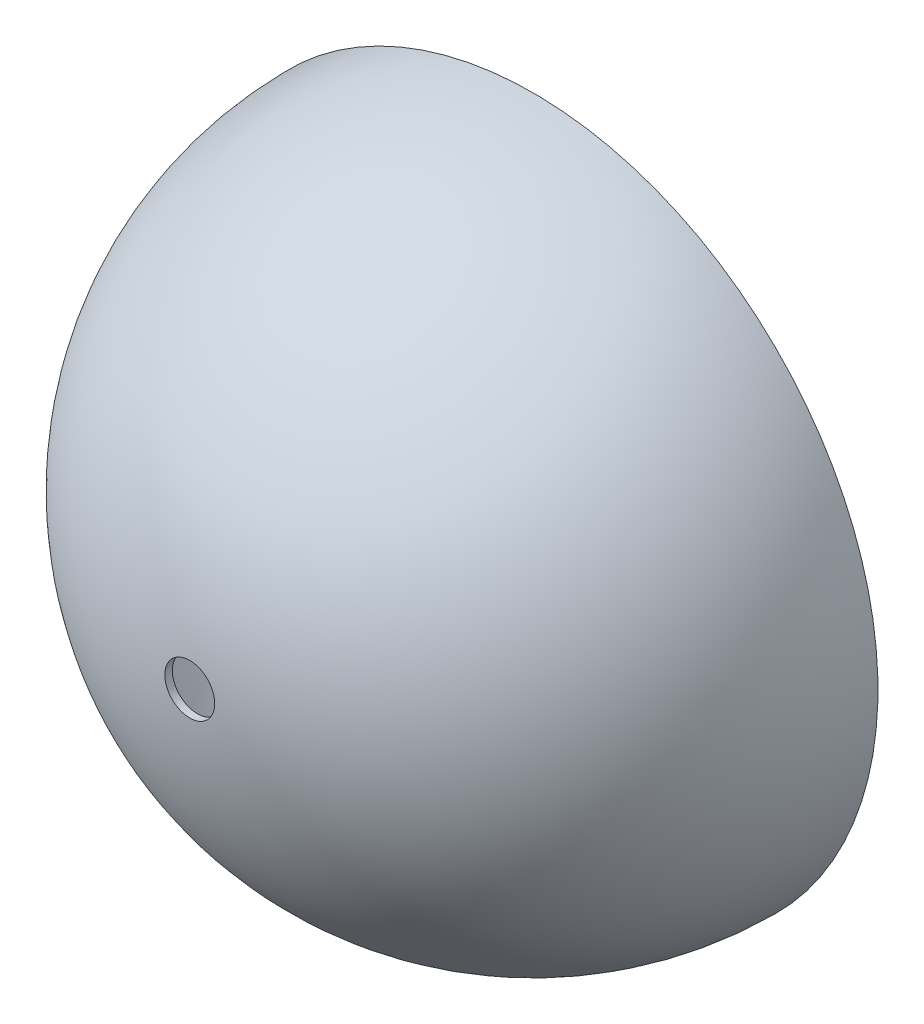
SolidWorks part; units mm, degrees
material "AISI 1035 Steel (SS)"
ref_plane "Front Plane" through (0, 0, 0) normal (0, 0, 1) x (1, 0, 0)
ref_plane "Top Plane" through (0, 0, 0) normal (0, 1, 0) x (1, 0, 0)
ref_plane "Right Plane" through (0, 0, 0) normal (1, 0, 0) x (0, 0, -1)
sketch "Sketch1" plane through (0, 0, 0) normal (0, 0, 1) x (1, 0, 0)
  line L0 (0, -690) -> (0, 690) construction
  line L1 (0, 690) -> (0, 675)
  line L2 (0, -675) -> (0, -690)
  arc A0 (0, -690) -> (0, 690) centre (0, 0) ccw
  arc A1 (0, -675) -> (0, 675) centre (0, 0) ccw
  point P4 (0, 0)
  dimension "D2" = 1350
  dimension "D1" = 1380
revolve "Revolve1" add sketch "Sketch1" angle 180 about L2
sketch "Sketch2" plane through (0, 0, 0) normal (0, 0, 1) x (1, 0, 0)
  circle A0 centre (0, 0) radius 50
  dimension "D1" = 100
extrude "Cut-Extrude5" cut sketch "Sketch2" against normal through all and the other way through all contours A0
